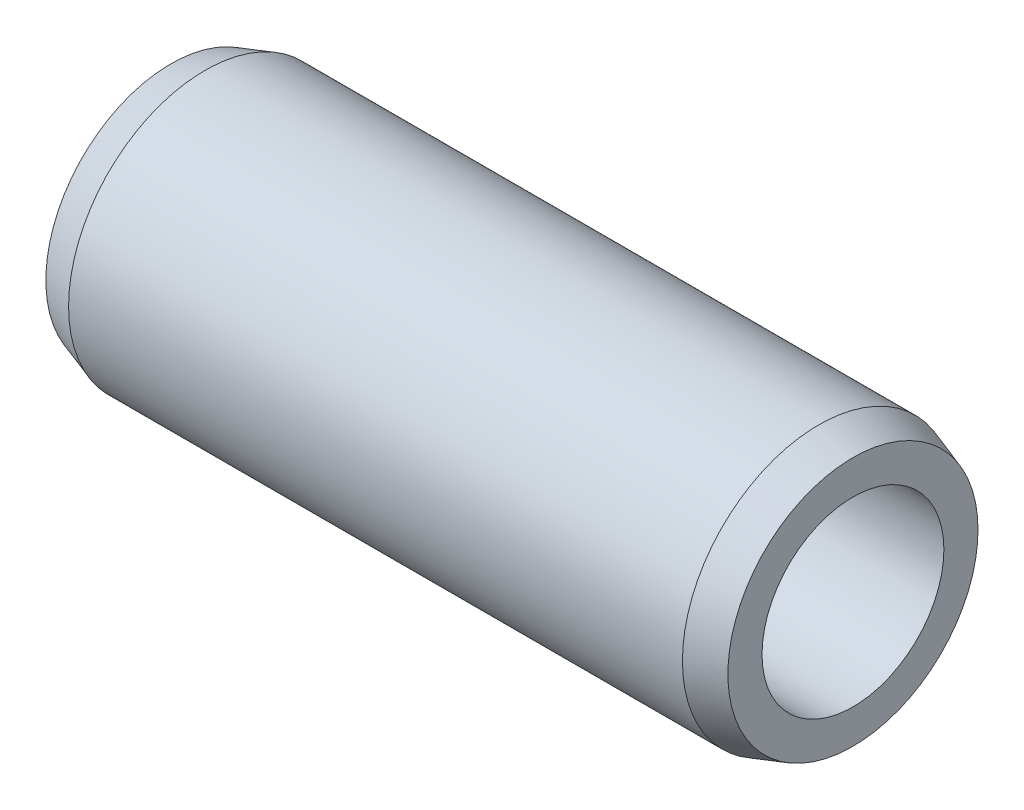
SolidWorks part; units mm, degrees
ref_plane "Front Plane" through (0, 0, 0) normal (0, 0, 1) x (1, 0, 0)
ref_plane "Top Plane" through (0, 0, 0) normal (0, 1, 0) x (1, 0, 0)
ref_plane "Right Plane" through (0, 0, 0) normal (1, 0, 0) x (0, 0, -1)
sketch "Sketch1" plane through (0, 0, 0) normal (1, 0, 0) x (0, 0, -1)
  circle A0 centre (0, 0) radius 6
  circle A1 centre (0, 0) radius 4
  dimension "D1" = 8
  dimension "D2" = 12
extrude "Boss-Extrude1" add sketch "Sketch1" along normal blind 30
chamfer "Chamfer2" distance 0.5 distance2 1.5 2 edges at (30, 0, -6) (0, 0, -6)
equation "\"d_inner\"= 8"
equation "\"d_outer\"= 12"
equation "\"l\"= 30"
equation "\"D1@Sketch1\"=\"d_inner\""
equation "\"D2@Sketch1\"=\"d_outer\""
equation "\"D1@Boss-Extrude1\"=\"l\""
